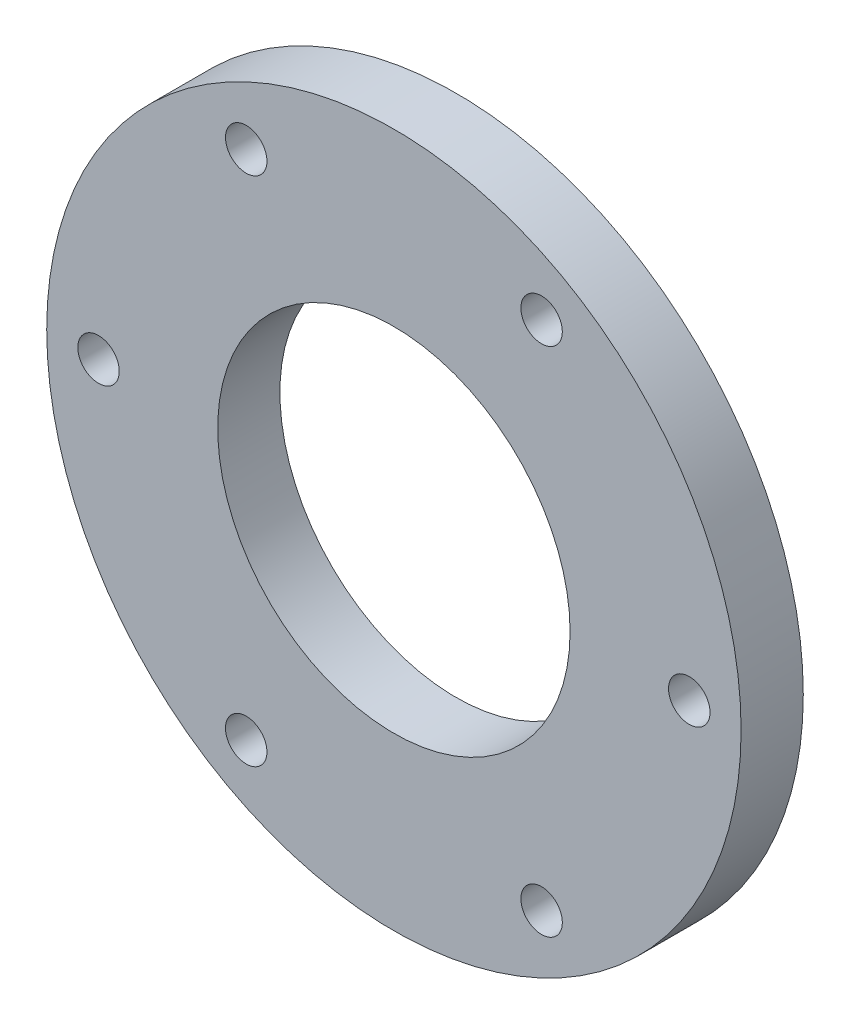
SolidWorks part; units mm, degrees
material "AISI 1045 Steel, cold drawn"
ref_plane "Front Plane" through (0, 0, 0) normal (0, 0, 1) x (1, 0, 0)
ref_plane "Top Plane" through (0, 0, 0) normal (0, 1, 0) x (1, 0, 0)
ref_plane "Right Plane" through (0, 0, 0) normal (1, 0, 0) x (0, 0, -1)
sketch "Sketch1" plane through (0, 0, 0) normal (0, 0, 1) x (1, 0, 0)
  circle A0 centre (0, 0) radius 33.5
  circle A1 centre (0, 0) radius 17
  dimension "D1" = 67
  dimension "D2" = 34
extrude "Boss-Extrude1" add sketch "Sketch1" along normal blind 6
sketch "Sketch2" plane through (0, 0, 0) normal (0, 0, -1) x (-1, 0, 0)
  circle A0 centre (0, 0) radius 28.5 construction
  circle A1 centre (0, 0) radius 28.5 construction
  circle A2 centre (0, 0) radius 28.5 construction
  circle A3 centre (0, 0) radius 28.5 construction
  circle A4 centre (0, 0) radius 28.5 construction
  circle A5 centre (0, 0) radius 28.5 construction
  point P3 (-28.5, 0)
  point P7 (-14.25, 24.6817)
  point P9 (14.25, 24.6817)
  point P11 (28.5, 0)
  point P13 (14.25, -24.6817)
  point P15 (-14.25, -24.6817)
  point P16 (0, 0)
  dimension "D1" = 57
  dimension "D2" = 6
hole_wizard "Ø4.0mm Dowel Hole1" positions "3DSketch1" profile "Sketch3" hole size "Ø4.0" standard "ISO"
sketch3d "3DSketch1"
  point P0 (28.5, 0, 0)
  point P3 (14.25, 24.6817, 0)
  point P6 (-14.25, 24.6817, 0)
  point P9 (-28.5, 0, 0)
  point P12 (-14.25, -24.6817, 0)
  point P15 (14.25, -24.6817, 0)
sketch "Sketch3" plane through (28.5, 0, 0) normal (1, 0, 0) x (0, 1, 0)
  line L0 (0, 0) -> (0, 25.7017)
  line L1 (0, 25.7017) -> (2, 24.5)
  line L2 (2, 24.5) -> (2, 0.025)
  line L3 (2, 0.025) -> (2.025, 0)
  line L5 (2.025, 0) -> (0, 0)
  line L6 (-2, 0.025) -> (-2.025, 0) construction
  line L10 (0, 25.7017) -> (-2, 24.5) construction
  line L11 (0, -6.35) -> (0, 107.95) construction
  dimension "Hole Dia." = 4
  dimension "Hole Depth" = 24.5
  dimension "Near C'Sink Dia." = 4.05
  dimension "Near C'Sink Angle" = 90
  dimension "Drill Angle" = 118
